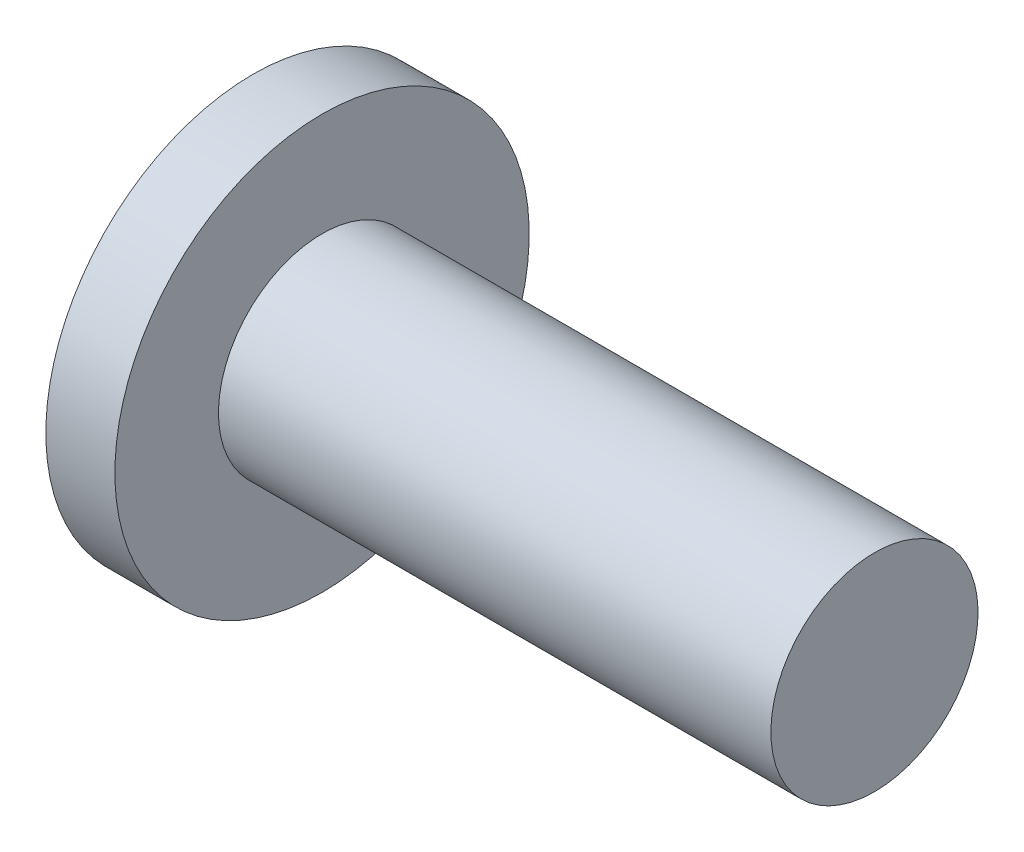
SolidWorks part; units mm, degrees
ref_plane "前视基准面" through (0, 0, 0) normal (0, 0, 1) x (1, 0, 0)
ref_plane "上视基准面" through (0, 0, 0) normal (0, 1, 0) x (1, 0, 0)
ref_plane "右视基准面" through (0, 0, 0) normal (1, 0, 0) x (0, 0, -1)
other "Configuration Table"
sketch "草图1" plane through (0, 0, 0) normal (0, 0, 1) x (1, 0, 0)
  line L0 (0, 0) -> (8, 0)
  line L1 (0, 0) -> (0, 1.5)
  line L2 (0, 1.5) -> (-1, 1.5)
  line L3 (8, 0) -> (8, -1.5)
  line L4 (8, -1.5) -> (6.7823, -1.5) construction
  line L5 (-1, 1.5) -> (-1, -1.5)
  line L6 (-1, -1.5) -> (8, -1.5)
  dimension "D1" = 8
  dimension "D2" = 1.5
  dimension "D3" = 1
  dimension "D4" = 1.5
revolve "旋转1" add sketch "草图1" angle 360 about L6
